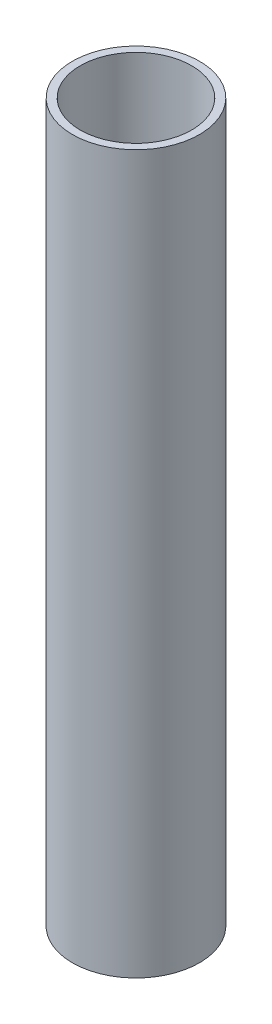
SolidWorks part; units mm, degrees
ref_plane "Front Plane" through (0, 0, 0) normal (0, 0, 1) x (1, 0, 0)
ref_plane "Top Plane" through (0, 0, 0) normal (0, 1, 0) x (1, 0, 0)
ref_plane "Right Plane" through (0, 0, 0) normal (1, 0, 0) x (0, 0, -1)
sketch "Sketch1" plane through (0, 0, 0) normal (0, 1, 0) x (1, 0, 0)
  circle A0 centre (0, 0) radius 3.1
  circle A1 centre (0, 0) radius 2.72
  dimension "D1" = 6.2
  dimension "D2" = 0.38
extrude "Boss-Extrude1" add sketch "Sketch1" along normal blind 35
